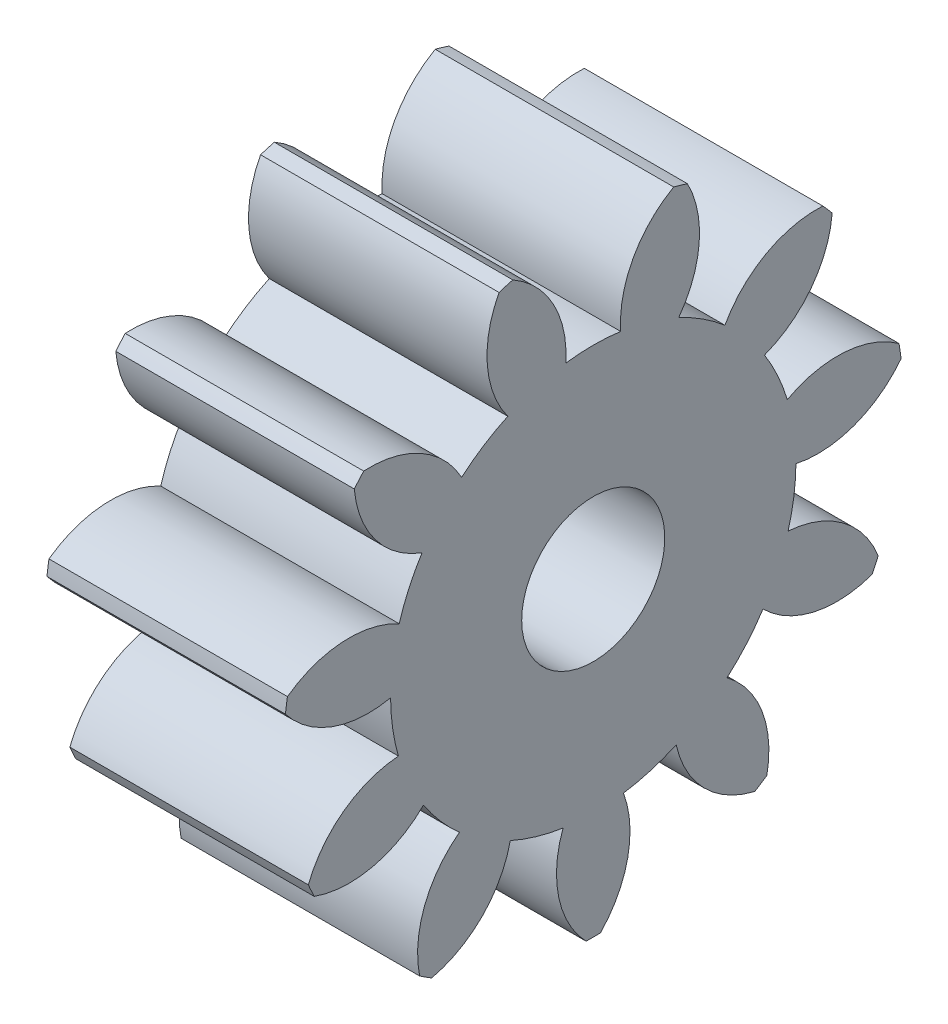
SolidWorks part; units mm, degrees
ref_plane "Plane1" through (0, 0, 0) normal (0, 0, 1) x (1, 0, 0)
ref_plane "Plane2" through (0, 0, 0) normal (0, 1, 0) x (1, 0, 0)
ref_plane "Plane3" through (0, 0, 0) normal (1, 0, 0) x (0, 0, -1)
sketch "HoldingSke" plane through (0, 0, 0) normal (0, 1, 0) x (1, 0, 0)
  line L0 (0, 0) -> (0.9816, -0.1908)
  line L1 (-15, 0) -> (100, 0) construction
  line L2 (0, 0) -> (-2.1039, 2.3779)
  line L3 (0, 0) -> (-11.863, 4.5341)
  line L4 (0, 0) -> (8.4773, 1.6478)
  line L5 (0, 0) -> (-46.8476, -17.4728)
  line L6 (0, 0) -> (-4.1448, -2.7965)
  line L7 (-2.1039, 2.3779) -> (8.6586, 51.2059)
  line L8 (-76.2, 54.61) -> (-75.7, 54.61)
  line L9 (-71.009, 38.7566) -> (-53.1078, 45.2721)
  line L10 (-76.2, 71.12) -> (104.1128, 71.12)
  line L11 (0, 0) -> (-5, 0)
  line L12 (-76.2, 101.6) -> (-76.162, 101.6)
  line L13 (24.9733, 27.94) -> (52.9518, 28.4284)
  line L14 (24.9733, 27.94) -> (24.9743, 27.94)
  line L15 (24.9733, 27.94) -> (100.4006, 29.5858)
  line L16 (-63.627, -1) -> (-12.827, -1)
  circle A0 centre (0, 0) radius 1.5
  circle A1 centre (0, 0) radius 4.249
  circle A2 centre (0, 0) radius 37.5
  circle A3 centre (0, 0) radius 1.5
  dimension "MHD" = 8.498
  dimension "Hub_dia" = 75
  dimension "Bore" = 3
  dimension "MBD" = 3
  dimension "Num_teeth" = 11
  dimension "Pitch" = 1
  dimension "Overall_len" = 50
  dimension "Show_teeth" = 11
  dimension "Thickness" = 5
  dimension "OAL" = 50.0001
  dimension "T_dim" = 0.5
  dimension "Ap" = 20
  dimension "H" = 19.05
  dimension "Pitch_radius" = 180.3128
  dimension "Width" = 5
  dimension "Backlash" = 0.038
  dimension "Addendum_fac" = 1
  dimension "Dedendum_fac" = 1.25
  dimension "Clearance_fac" = 0.25
  dimension "Dedendum_add" = 0.001
  dimension "Module" = 1
sketch "BasProSke" plane through (0, 0, 0) normal (0, 1, 0) x (1, 0, 0)
  line L0 (-10, 0) -> (60, 0) construction
  line L1 (0, 0) -> (0, 6.5)
  line L2 (0, 0) -> (5, 0)
  line L3 (5, 0) -> (5, 6.5)
  line L4 (5, 6.5) -> (0, 6.5)
  dimension "Thickness" = 5
  dimension "Diameter" = 13
revolve "Base-Revolve" add sketch "BasProSke" angle 360 about L0
sketch "TooCutSke" plane through (0, 0, 0) normal (1, 0, 0) x (0, 0, -1)
  line L1 (0, 0) -> (0, 107) construction
  line L2 (0, 0) -> (-0.8491, 5.4341) construction
  line L3 (0, 0) -> (-3.0727, 10.4645) construction
  line L4 (-0.8491, 5.4341) -> (-1.5363, 5.2323) construction
  arc A0 (0.576, 4.2098) -> (-0.576, 4.2098) centre (0, 0) ccw
  arc A1 (1.7187, 6.295) -> (-1.7187, 6.295) centre (0, 0) ccw
  circle A2 centre (0, 0) radius 5.5 construction
  circle A3 centre (0, 0) radius 5.1683 construction
  arc A4 (-0.576, 4.2098) -> (-1.7187, 6.295) centre (-2.7707, 4.3629) ccw
  arc A5 (1.7187, 6.295) -> (0.576, 4.2098) centre (2.7707, 4.3629) ccw
  dimension "Root_dia" = 8.498
  dimension "Overcut_dia" = 13.0508
  dimension "Pitch_dia" = 11
  dimension "Base_dia" = 10.3366
  dimension "Flank_rad" = 2.2
  dimension "Half_ang" = 16.364
  dimension "Half_CT" = 0.7162
extrude "ToothCut" cut sketch "TooCutSke" along normal through all
fillet "Breaks" [suppressed] radius 0.02
fillet "RootFillets" [suppressed] radius 0.251
pattern_circular "TeethCuts" count 11 every 32.727 about axis through (-10, 0, 0) along (1, 0, 0) of "ToothCut", "RootFillets", "Breaks"
sketch "HubNeaOneSke" plane through (0, 0, 0) normal (-1, 0, 0) x (0, 0, 1)
  circle A0 centre (0, 0) radius 4.249
  dimension "Diameter" = 8.498
extrude "HubNearOne" [suppressed] add sketch "HubNeaOneSke" along normal blind 45.0001
sketch "HubNeaBotSke" plane through (0, 0, 0) normal (-1, 0, 0) x (0, 0, 1)
  circle A0 centre (0, 0) radius 4.249
  dimension "Diameter" = 8.498
extrude "HubNearBoth" [suppressed] add sketch "HubNeaBotSke" along normal blind 22.5
ref_plane "FarPln" through (5, 0, 0) normal (1, 0, 0) x (0, 0, -1)
sketch "HubFarSke" plane through (5, 0, 0) normal (1, 0, 0) x (0, 0, -1)
  circle A0 centre (0, 0) radius 4.249
  dimension "Diameter" = 8.498
extrude "HubFar" [suppressed] add sketch "HubFarSke" along normal blind 22.5
sketch "BorSke" plane through (0, 0, 0) normal (1, 0, 0) x (0, 0, -1)
  circle A0 centre (0, 0) radius 1.5
  dimension "Diameter" = 3
extrude "Bore" cut sketch "BorSke" along normal mid plane 100.0001
sketch "KeySke" plane through (0, 0, 0) normal (1, 0, 0) x (0, 0, -1)
  line L0 (-0.6, 0) -> (-0.6, 2)
  line L1 (-0.6, 2) -> (0.6, 2)
  line L2 (0.6, 2) -> (0.6, 0)
  line L3 (0, 0) -> (0, 34) construction
  line L4 (-0.6, 0) -> (0.6, 0)
  dimension "Offset" = 2
  dimension "Width" = 1.2
extrude "Keyway" [suppressed] cut sketch "KeySke" along normal mid plane 100.0001
pattern_circular "Keyway2" [suppressed] count 2 every 90 about axis through (-10, 0, 0) along (1, 0, 0)
sketch "Esquisse1" plane through (0, 0, 0) normal (-1, 0, 0) x (0, 0, 1)
  circle A0 centre (0, 0) radius 2.75
  dimension "D1" = 5.5
extrude "Enlèv. mat.-Extru.1" cut sketch "Esquisse1" against normal blind 3
sketch "Esquisse2" plane through (3, 0, 0) normal (-1, 0, 0) x (0, 0, 1)
  circle A0 centre (0, 0) radius 1.5
  circle A1 centre (0, 0) radius 2.75
extrude "Boss.-Extru.1" add sketch "Esquisse2" along normal up to surface (3 mm away) up to face at (0, 0, 2.75)
sketch "Esquisse3" plane through (0, 0, 0) normal (-1, 0, 0) x (0, 0, 1)
  line L1 (2.3814, -2.1868) -> (3.0845, 0.969)
  line L2 (3.0845, 0.969) -> (0.7031, 3.1558)
  line L3 (0.7031, 3.1558) -> (-2.3814, 2.1868)
  line L4 (-2.3814, 2.1868) -> (-3.0845, -0.969)
  line L5 (-3.0845, -0.969) -> (-0.7031, -3.1558)
  line L6 (-0.7031, -3.1558) -> (2.3814, -2.1868)
  circle A0 centre (0, 0) radius 2.8 construction
  dimension "D1" = 5.6
extrude "Enlèv. mat.-Extru.2" cut sketch "Esquisse3" against normal blind 2
sketch "Esquisse4" plane through (0, 0, 0) normal (-1, 0, 0) x (0, 0, 1)
  circle A0 centre (0, 0) radius 3.3011
  circle A1 centre (0, 0) radius 1.5
extrude "Boss.-Extru.2" add sketch "Esquisse4" against normal up to surface (2 mm away) up to face at (2, 0, 1.5)
sketch "Esquisse5" plane through (0, 0, 0) normal (-1, 0, 0) x (0, 0, 1)
  line L0 (-1.6151, 2.4146) -> (2.8726, 0.4329)
  arc A0 (-1.6151, 2.4146) -> (2.8726, 0.4329) centre (0, 0) ccw
  dimension "D1" = 5.81
extrude "Enlèv. mat.-Extru.3" cut sketch "Esquisse5" against normal blind 2.5
equation "' \"Module@HoldingSke\" = 6.35"
equation "' \"Num_teeth@HoldingSke\" = 12"
equation "' \"Ap@HoldingSke\" =  20"
equation "' \"Ap@HoldingSke\" = 20"
equation "' \"Width@HoldingSke\" = 0.5 * 25.4"
equation "' \"Hub_dia@HoldingSke\"= 1 * 25.4"
equation "' \"Hub_dia@HoldingSke\" = 1 * 25.4"
equation "' \"Overall_len@HoldingSke\" = 1.0 * 25.4"
equation "' \"Bore@HoldingSke\" = 0.75 * 25.4"
equation "' \"T_dim@HoldingSke\" = 0.1 * 25.4"
equation "' \"Width@KeySke\" = 0.25 * 25.4"
equation "' \"Show_teeth@HoldingSke\" = 13"
equation "' \"Backlash@HoldingSke\" = 0.009 * 25.4"
equation "' \"Addendum_fac@HoldingSke\" = 1.0"
equation "' \"Dedendum_fac@HoldingSke\" = 1.25"
equation "' \"Dedendum_add@HoldingSke\" = 0.00005 * 25.4"
equation "' \"Clearance_fac@HoldingSke\" = 0.25"
equation "\"Pitch@HoldingSke\" = 1 / \"Module@HoldingSke\""
equation "\"Overcut_dia@TooCutSke\" = (\"Num_teeth@HoldingSke\" + 2 * \"Addendum_fac@HoldingSke\") / \"Pitch@HoldingSke\" + 0.002 * 25.4"
equation "\"Pitch_dia@TooCutSke\" = \"Num_teeth@HoldingSke\" / \"Pitch@HoldingSke\""
equation "\"Base_dia@TooCutSke\" = \"Num_teeth@HoldingSke\" / \"Pitch@HoldingSke\" * cos((\"Ap@HoldingSke\"  * 3.14159265 / 180))"
equation "\"Root_dia@TooCutSke\" = (\"Num_teeth@HoldingSke\" + 2) / \"Pitch@HoldingSke\" - 2 * (\"Addendum_fac@HoldingSke\" + \"Dedendum_fac@HoldingSke\") / \"Pitch@HoldingSke\" - \"Dedendum_add@HoldingSke\" * 2"
equation "\"Half_ang@TooCutSke\" = 180 / \"Num_teeth@HoldingSke\""
equation "\"Half_CT@TooCutSke\" = \"Num_teeth@HoldingSke\" / \"Pitch@HoldingSke\" * sin((3.14159265 / 2 / \"Num_teeth@HoldingSke\")) / 2 - 7 * \"Backlash@HoldingSke\" / 4"
equation "\"Flank_rad@TooCutSke\" = \"Num_teeth@HoldingSke\" / \"Pitch@HoldingSke\" / 5"
equation "\"Radius@RootFillets\" = \"Clearance_fac@HoldingSke\" / \"Pitch@HoldingSke\" + \"Dedendum_add@HoldingSke\""
equation "\"Break_rad@Breaks\" = 0.02 / \"Pitch@HoldingSke\""
equation "\"Thickness@HoldingSke\" = \"Width@HoldingSke\""
equation "\"OAL@HoldingSke\" = \"Thickness@HoldingSke\""
equation "\"MHD@HoldingSke\" = (\"Num_teeth@HoldingSke\" + 2) / \"Pitch@HoldingSke\" - 2 * (\"Addendum_fac@HoldingSke\" + \"Dedendum_fac@HoldingSke\")  / \"Pitch@HoldingSke\" - \"Dedendum_add@HoldingSke\" * 2"
equation "\"MBD@HoldingSke\" = (\"Num_teeth@HoldingSke\" + 2) / \"Pitch@HoldingSke\" - 2 * (\"Addendum_fac@HoldingSke\" + \"Dedendum_fac@HoldingSke\")  / \"Pitch@HoldingSke\" - \"Dedendum_add@HoldingSke\" * 2 - 0.002 * 25.4"
equation "\"MHD@HoldingSke\" = ((sgn( \"MHD@HoldingSke\" - \"Hub_dia@HoldingSke\" )-1)*( \"MHD@HoldingSke\" - \"Hub_dia@HoldingSke\" ))/-2+ \"Hub_dia@HoldingSke\""
equation "\"MBD@HoldingSke\" = ((sgn( \"MBD@HoldingSke\" - \"Bore@HoldingSke\" )-1)*( \"MBD@HoldingSke\" - \"Bore@HoldingSke\" ))/-2+ \"Bore@HoldingSke\""
equation "\"OAL@HoldingSke\" = ((sgn( \"OAL@HoldingSke\" - \"Overall_len@HoldingSke\" )+1)*( \"OAL@HoldingSke\" - \"Overall_len@HoldingSke\" ))/2 + \"Overall_len@HoldingSke\" + 0.000002 * 25.4"
equation "\"Num_teeth@TeethCuts\" = int( \"Show_teeth@HoldingSke\" ) + 1"
equation "\"Num_teeth@TeethCuts\" = ((sgn( \"Num_teeth@TeethCuts\" - \"Num_teeth@HoldingSke\" )-1)*( \"Num_teeth@TeethCuts\" - \"Num_teeth@HoldingSke\" ))/-2+ \"Num_teeth@HoldingSke\""
equation "\"Num_teeth@TeethCuts\" = ((sgn( \"Num_teeth@TeethCuts\" - 2.0)+1)*( \"Num_teeth@TeethCuts\" - 2.0))/2 +2.0"
equation "\"Angle@TeethCuts\" = 360.0 / \"Num_teeth@HoldingSke\""
equation "\"Diameter@BasProSke\" = (\"Num_teeth@HoldingSke\" + 2 * \"Addendum_fac@HoldingSke\") / \"Pitch@HoldingSke\""
equation "\"Thickness@BasProSke\"  = \"Thickness@HoldingSke\""
equation "' \"Fillet_rad@BasProSke\" =  \"Thickness@HoldingSke\" * 0.05"
equation "' \"Fillet_rad@BasProSke\" = \"Thickness@HoldingSke\" * 0.05"
equation "\"MHD@HoldingSke\" = ((sgn( \"MHD@HoldingSke\" - \"Root_dia@TooCutSke\" )-1)*( \"MHD@HoldingSke\" - \"Root_dia@TooCutSke\" ))/-2+ \"Root_dia@TooCutSke\""
equation "\"Diameter@HubNeaOneSke\" = \"MHD@HoldingSke\""
equation "\"Length@HubNearOne\" = \"OAL@HoldingSke\" - \"Thickness@BasProSke\""
equation "\"Diameter@HubNeaBotSke\" = \"MHD@HoldingSke\""
equation "\"Length@HubNearBoth\" = ( \"OAL@HoldingSke\" - \"Thickness@BasProSke\" ) / 2.0"
equation "\"Thickness@FarPln\" = \"Thickness@BasProSke\""
equation "\"Diameter@HubFarSke\" = \"MHD@HoldingSke\""
equation "\"Length@HubFar\" = ( \"OAL@HoldingSke\" - \"Thickness@BasProSke\" ) / 2.0"
equation "\"Diameter@BorSke\" = \"MBD@HoldingSke\""
equation "\"D1@Bore\" = \"OAL@HoldingSke\" * 2.0"
equation "\"D1@Keyway\" = \"OAL@HoldingSke\" * 2.0"
equation "\"Offset@KeySke\" = \"T_dim@HoldingSke\" + \"MBD@HoldingSke\" / 2.0"
